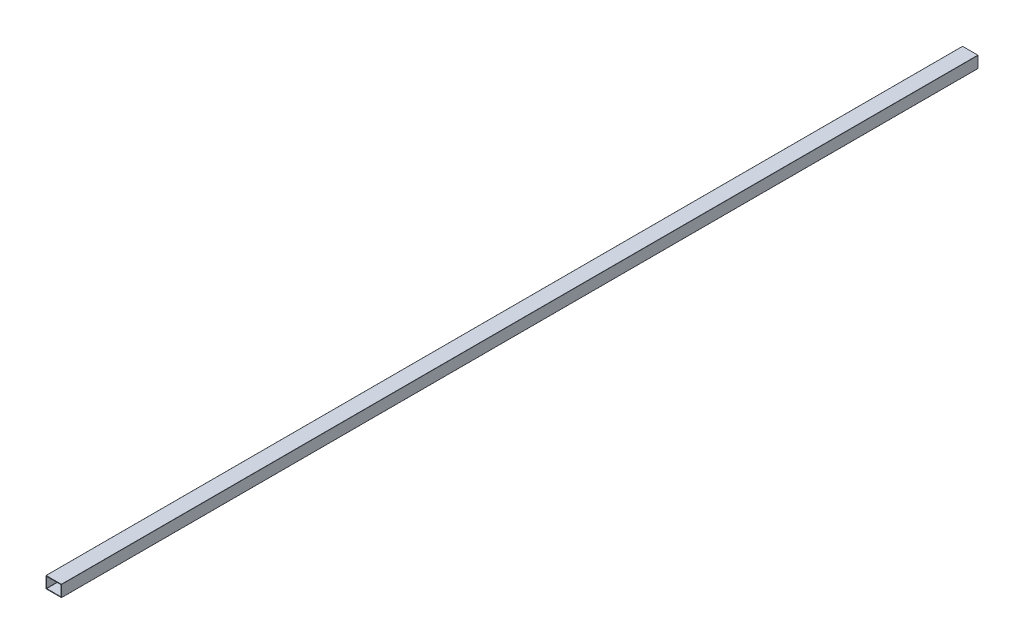
SolidWorks part; units mm, degrees
material "AISI 1035 Acero (SS)"
ref_plane "Alzado" through (0, 0, 0) normal (0, 0, 1) x (1, 0, 0)
ref_plane "Planta" through (0, 0, 0) normal (0, 1, 0) x (1, 0, 0)
ref_plane "Vista lateral" through (0, 0, 0) normal (1, 0, 0) x (0, 0, -1)
sketch "Croquis1" plane through (0, 0, 0) normal (0, 0, 1) x (1, 0, 0)
  line L0 (-47, -34.3) -> (-47, 34.3)
  line L1 (-50.8, -38.1) -> (50.8, -38.1)
  line L2 (-50.8, -38.1) -> (-50.8, 38.1)
  line L3 (-50.8, 38.1) -> (50.8, 38.1)
  line L4 (50.8, -38.1) -> (50.8, 38.1)
  line L5 (-50.8, -38.1) -> (50.8, 38.1) construction
  line L6 (-50.8, 38.1) -> (50.8, -38.1) construction
  line L7 (-47, 34.3) -> (47, 34.3)
  line L8 (47, -34.3) -> (47, 34.3)
  line L9 (-47, -34.3) -> (47, -34.3)
  point P0 (0, 0)
  dimension "D1" = 76.2
  dimension "D2" = 101.6
  dimension "D3" = 3.8
extrude "Saliente-Extruir1" add sketch "Croquis1" against normal blind 6000
fillet "Redondeo1" radius 1 8 edges at (-47, 34.3, -3000) (47, 34.3, -3000) (47, -34.3, -3000) (-50.8, -38.1, -3000) (-50.8, 38.1, -3000) (-47, -34.3, -3000) (50.8, -38.1, -3000) (50.8, 38.1, -3000)
